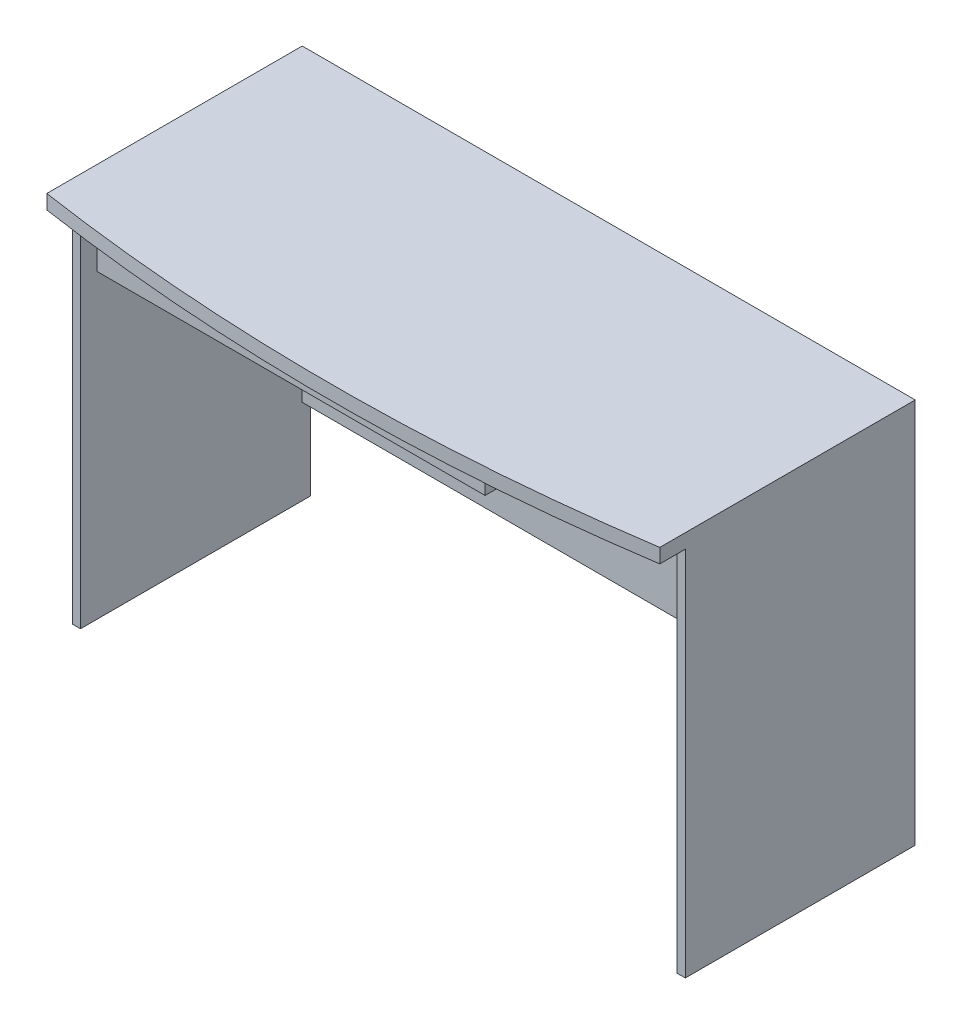
SolidWorks part; units mm, degrees
ref_plane "Front Plane" through (0, 0, 0) normal (0, 0, 1) x (1, 0, 0)
ref_plane "Top Plane" through (0, 0, 0) normal (0, 1, 0) x (1, 0, 0)
ref_plane "Right Plane" through (0, 0, 0) normal (1, 0, 0) x (0, 0, -1)
sketch "Sketch1" plane through (0, 0, 0) normal (0, 1, 0) x (1, 0, 0)
  line L0 (-600, -250) -> (600, -250) construction
  line L2 (-600, -250) -> (-600, 250)
  line L3 (-600, 250) -> (600, 250)
  line L4 (600, -250) -> (600, 250)
  line L5 (-600, -250) -> (600, 250) construction
  line L6 (-600, 250) -> (600, -250) construction
  arc A0 (-600, -250) -> (600, -250) centre (0, 3727.5) ccw
  point P0 (0, 0)
  point P7 (0, -250)
  dimension "D3" = 45
  dimension "D1" = 1200
  dimension "D2" = 500
extrude "Boss-Extrude1" add sketch "Sketch1" along normal blind 28
sketch "Sketch2" plane through (0, 0, 0) normal (0, -1, 0) x (1, 0, 0)
  line L1 (-600, -250) -> (-584, -250)
  line L2 (-600, -250) -> (-600, 200)
  line L3 (-600, 200) -> (-584, 200)
  line L4 (-584, -250) -> (-584, 200)
  dimension "D1" = 450
  dimension "D2" = 16
extrude "Boss-Extrude2" add sketch "Sketch2" along normal blind 727
mirror "Mirror1" about plane through (0, 0, 0) normal (1, 0, 0) of "Boss-Extrude2"
sketch "Sketch3" plane through (-584, 0, 0) normal (1, 0, 0) x (0, 0, -1)
  line L0 (250, -727) -> (250, 0) construction
  line L1 (250, -260) -> (234, -260)
  line L2 (250, -260) -> (250, -560)
  line L3 (250, -560) -> (234, -560)
  line L4 (234, -260) -> (234, -560)
  line L5 (250, 0) -> (-200, 0) construction
  dimension "D1" = 16
  dimension "D2" = 300
  dimension "D3" = 260
extrude "Boss-Extrude3" add sketch "Sketch3" along normal up to surface (1168 mm away) up to face at (584, -363.5, -25)
sketch "Sketch4" plane through (0, 0, 0) normal (0, -1, 0) x (1, 0, 0)
  line L0 (-584, -250) -> (-584, 200) construction
  line L1 (-517, 235) -> (243, 235)
  line L2 (-517, 235) -> (-517, -195)
  line L3 (-517, -195) -> (243, -195)
  line L4 (243, 235) -> (243, -195)
  line L5 (584, -250) -> (-584, -250) construction
  dimension "D1" = 67
  dimension "D2" = 760
  dimension "D3" = 430
  dimension "D4" = 55
extrude "Boss-Extrude4" add sketch "Sketch4" along normal blind 70
